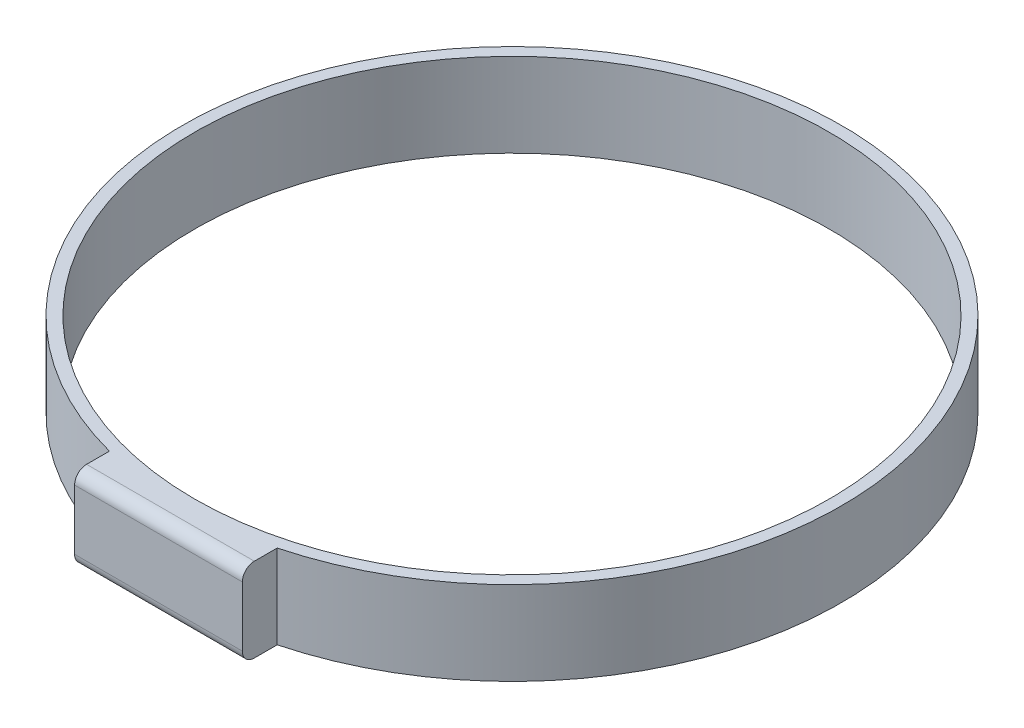
SolidWorks part; units mm, degrees
material "AISI 316 Stainless Steel Sheet (SS)"
ref_plane "Front Plane" through (0, 0, 0) normal (0, 0, 1) x (1, 0, 0)
ref_plane "Top Plane" through (0, 0, 0) normal (0, 1, 0) x (1, 0, 0)
ref_plane "Right Plane" through (0, 0, 0) normal (1, 0, 0) x (0, 0, -1)
sketch "Sketch1" plane through (0, 0, 0) normal (0, 1, 0) x (1, 0, 0)
  circle A0 centre (0, 0) radius 26.5
  circle A1 centre (0, 0) radius 27.5
  dimension "D1" = 53
  dimension "D2" = 1
extrude "Boss-Extrude1" add sketch "Sketch1" along normal blind 7
ref_plane "Plane1" through (0, 0, 26.5) normal (0, 0, 1) x (1, 0, 0)
sketch "Sketch2" plane through (0, 0, 26.5) normal (0, 0, 1) x (1, 0, 0)
  line L0 (26.5, 7) -> (-26.5, 7) construction
  line L1 (-7, 7) -> (7, 7)
  line L2 (-7, 7) -> (-7, 0)
  line L3 (-7, 0) -> (7, 0)
  line L4 (7, 7) -> (7, 0)
  line L5 (-27.5, 0) -> (27.5, 0) construction
  dimension "D1" = 14
extrude "Boss-Extrude2" add sketch "Sketch2" along normal blind 3
fillet "Fillet1" radius 1 2 edges at (0, 0, 29.5) (0, 7, 29.5)
